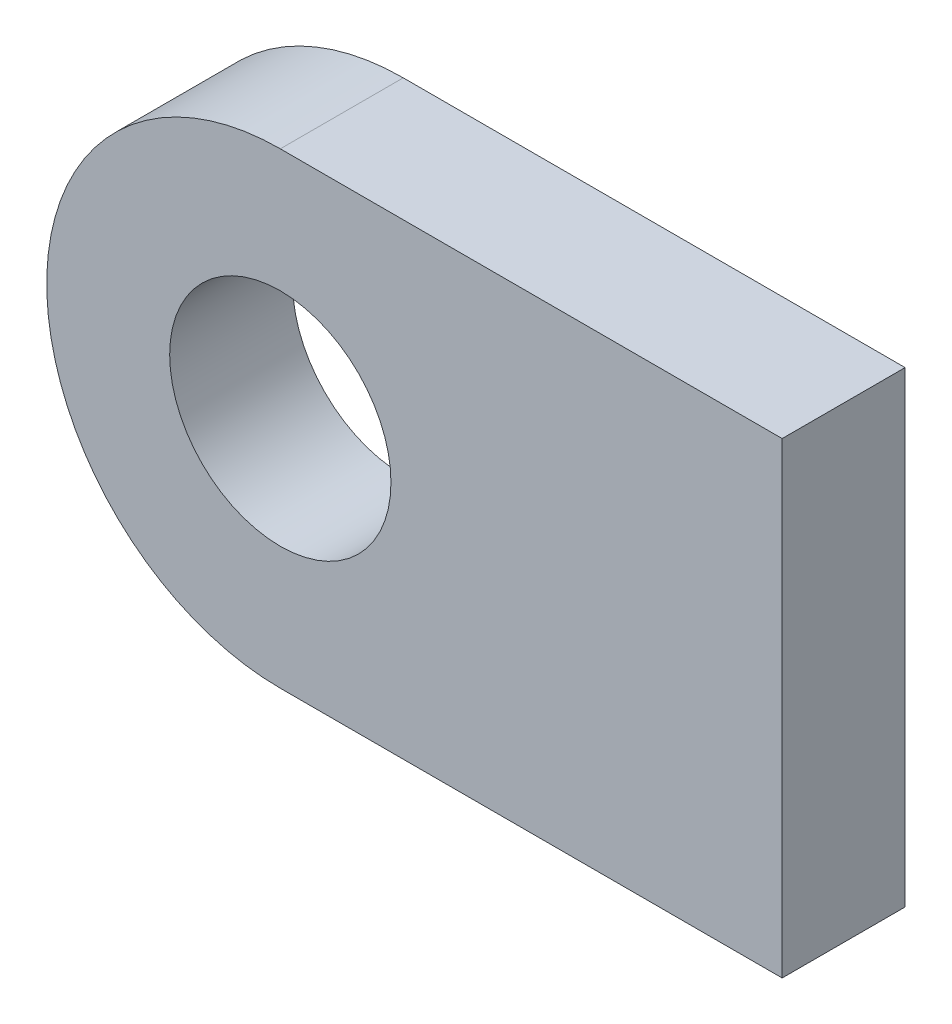
SolidWorks part; units mm, degrees
ref_plane "Front Plane" through (0, 0, 0) normal (0, 0, 1) x (1, 0, 0)
ref_plane "Top Plane" through (0, 0, 0) normal (0, 1, 0) x (1, 0, 0)
ref_plane "Right Plane" through (0, 0, 0) normal (1, 0, 0) x (0, 0, -1)
sketch "Sketch1" plane through (0, 0, 0) normal (0, 0, 1) x (1, 0, 0)
  line L0 (0, 9.5) -> (20.41, 9.5)
  line L1 (20.41, 9.5) -> (20.41, -9.5)
  line L2 (20.41, -9.5) -> (0, -9.5)
  circle A0 centre (0, 0) radius 4.5
  arc A1 (0, 9.5) -> (0, -9.5) centre (0, 0) ccw
  arc A2 (0, -9.5) -> (0, 9.5) centre (0, 0) ccw construction
  circle A3 centre (0, 0) radius 9.5 construction
  dimension "D1" = 9
  dimension "D3" = 20.41
  dimension "D2" = 5
extrude "Boss-Extrude1" add sketch "Sketch1" along normal mid plane 5
